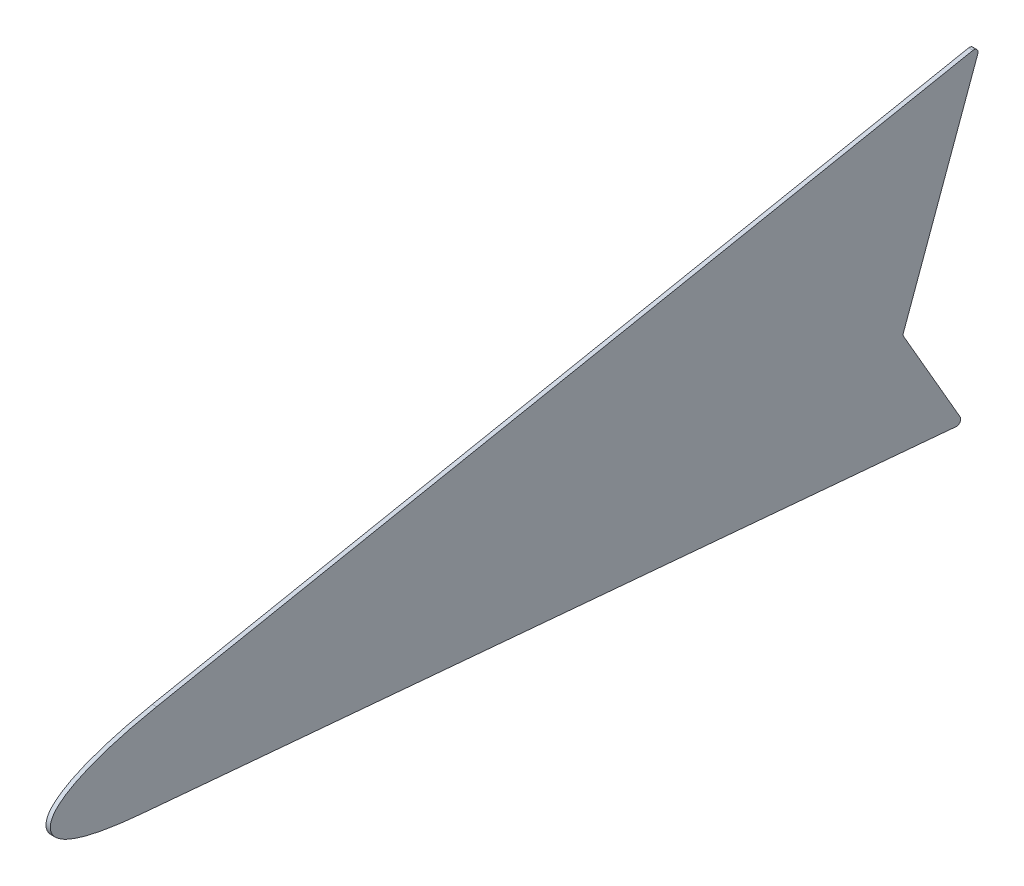
SolidWorks part; units mm, degrees
material "Maple"
ref_plane "Front Plane" through (0, 0, 0) normal (0, 0, 1) x (1, 0, 0)
ref_plane "Top Plane" through (0, 0, 0) normal (0, 1, 0) x (1, 0, 0)
ref_plane "Right Plane" through (0, 0, 0) normal (1, 0, 0) x (0, 0, -1)
other "Configuration Table"
sketch "airfoil" plane through (0, 0, 0) normal (1, 0, 0) x (0, 0, -1)
  line L0 (0, 0) -> (0, -24764.0796) construction
  line L1 (0, 0) -> (24764.0796, 0) construction
  line L2 (400, -0.019) -> (400, -24764.0986) construction
  spline S1 degree 3 poles (399.7808, 0.0037) (400.0541, -0.007) (399.7873, 0.0524) (399.5698, 0.1247) (399.0314, 0.2681) (398.361, 0.4579) (397.4667, 0.704) (396.3877, 1.0028) (395.1106, 1.354) (393.6412, 1.7553) (391.9797, 2.2075) (390.1273, 2.7067) (388.0863, 3.2534) (385.8581, 3.8449) (383.445, 4.48) (380.8487, 5.1558) (378.0717, 5.8707) (375.117, 6.6232) (371.9868, 7.4101) (368.6841, 8.23) (365.2117, 9.0791) (361.5733, 9.9574) (357.7717, 10.8596) (353.8109, 11.785) (349.6943, 12.7299) (345.4261, 13.6926) (341.0101, 14.67) (336.4505, 15.6593) (331.7515, 16.6575) (326.9179, 17.6633) (321.9541, 18.6731) (316.8647, 19.6833) (311.6551, 20.6931) (306.3302, 21.6989) (300.8951, 22.6978) (295.3553, 23.6882) (289.7158, 24.6666) (283.9826, 25.6307) (278.1611, 26.5781) (272.2574, 27.5067) (266.277, 28.413) (260.2261, 29.2967) (254.1107, 30.1529) (247.9371, 30.9818) (241.7114, 31.7791) (235.4401, 32.5443) (229.1296, 33.2746) (222.786, 33.9673) (216.4162, 34.6219) (210.0263, 35.2355) (203.6235, 35.8067) (197.2141, 36.3341) (190.8047, 36.8153) (184.4021, 37.2494) (178.0131, 37.6354) (171.6442, 37.9712) (165.2972, 38.2548) (158.9505, 38.4929) (152.6099, 38.6533) (146.2875, 38.7333) (140.0186, 38.732) (133.8104, 38.6513) (127.6704, 38.4892) (121.6052, 38.2488) (115.622, 37.93) (109.7277, 37.5349) (103.9291, 37.065) (98.2328, 36.5217) (92.6455, 35.9077) (87.1737, 35.2252) (81.8233, 34.4776) (76.6008, 33.6657) (71.5116, 32.7951) (66.562, 31.8667) (61.7572, 30.8857) (57.1026, 29.8545) (52.6032, 28.7774) (48.2641, 27.6573) (44.0894, 26.4993) (40.084, 25.3064) (36.2515, 24.0838) (32.5965, 22.8336) (29.1219, 21.5618) (25.8316, 20.271) (22.7281, 18.9666) (19.8149, 17.6508) (17.0939, 16.3288) (14.5679, 15.0036) (12.239, 13.6786) (10.1085, 12.3581) (8.1785, 11.044) (6.4499, 9.7401) (4.9234, 8.4488) (3.6003, 7.1722) (2.4808, 5.9125) (1.5655, 4.6706) (0.8549, 3.4474) (0.3497, 2.2432) (0.0528, 1.0583) (-0.034, -0.1055) (0.0897, -1.2398) (0.4182, -2.3322) (0.9504, -3.3701) (1.6818, -4.3459) (2.6067, -5.2617) (3.7234, -6.1177) (5.0287, -6.9169) (6.5216, -7.6597) (8.2002, -8.347) (10.0619, -8.981) (12.1056, -9.5604) (14.3281, -10.088) (16.7275, -10.5633) (19.3007, -10.9868) (22.0447, -11.3609) (24.9566, -11.6853) (28.0329, -11.9614) (31.2705, -12.1904) (34.666, -12.3741) (38.2157, -12.5133) (41.9161, -12.6098) (45.7634, -12.6653) (49.7535, -12.6809) (53.883, -12.66) (58.1475, -12.6026) (62.5433, -12.5119) (67.0662, -12.39) (71.7121, -12.2398) (76.4768, -12.062) (81.3559, -11.86) (86.3452, -11.6366) (91.4405, -11.3942) (96.6373, -11.1349) (101.9311, -10.8619) (107.3173, -10.5778) (112.7915, -10.2853) (118.3489, -9.9879) (123.9847, -9.6861) (129.6945, -9.386) (135.4732, -9.0873) (141.316, -8.7944) (147.2177, -8.5093) (153.1732, -8.2342) (159.2057, -7.9715) (165.3147, -7.7212) (171.4933, -7.4556) (177.7074, -7.1838) (183.946, -6.9064) (190.2032, -6.6255) (196.473, -6.3423) (202.7491, -6.0574) (209.0254, -5.7741) (215.296, -5.4912) (221.5545, -5.212) (227.795, -4.937) (234.0111, -4.666) (240.1968, -4.4016) (246.3459, -4.1434) (252.4524, -3.8927) (258.5098, -3.6496) (264.5124, -3.4153) (270.4539, -3.1894) (276.3284, -2.9725) (282.1299, -2.7653) (287.8522, -2.5667) (293.4898, -2.3784) (299.0368, -2.1995) (304.4876, -2.0293) (309.8363, -1.8692) (315.0775, -1.7173) (320.2055, -1.5749) (325.2152, -1.441) (330.1011, -1.3159) (334.8582, -1.1978) (339.4816, -1.088) (343.9662, -0.9862) (348.3071, -0.89) (352.4999, -0.8021) (356.5399, -0.7188) (360.4229, -0.6427) (364.1446, -0.5721) (367.7011, -0.5068) (371.0883, -0.4463) (374.3025, -0.3909) (377.3402, -0.34) (380.1983, -0.2931) (382.8734, -0.2506) (385.3625, -0.2117) (387.6629, -0.1765) (389.7721, -0.1455) (391.6876, -0.117) (393.4074, -0.0923) (394.9291, -0.0701) (396.2527, -0.0522) (397.3716, -0.0354) (398.2989, -0.0246) (398.9952, -0.0113) (399.5522, -0.0105) (399.7808, 0.0037) (400.0541, -0.007) (399.7873, 0.0524) knots -0.001127 -0.000501 -0.000125 0 0.000125 0.000501 0.001127 0.002002 0.003126 0.004497 0.006113 0.007974 0.010078 0.012421 0.015002 0.017818 0.020866 0.024143 0.027646 0.03137 0.035312 0.039469 0.043836 0.048408 0.05318 0.058149 0.063308 0.068652 0.074177 0.079876 0.085744 0.091775 0.097962 0.1043 0.110782 0.117401 0.124151 0.131025 0.138017 0.145118 0.152322 0.159622 0.167011 0.17448 0.182023 0.189631 0.197298 0.205015 0.212775 0.220569 0.228391 0.236232 0.244084 0.251939 0.25979 0.267629 0.275447 0.283237 0.290992 0.298721 0.306502 0.314226 0.321883 0.329466 0.336969 0.344383 0.351701 0.358917 0.366023 0.373012 0.379878 0.386613 0.393211 0.399667 0.405973 0.412124 0.418114 0.423937 0.429588 0.435061 0.440352 0.445457 0.45037 0.455088 0.459606 0.463923 0.468034 0.471937 0.475631 0.479114 0.482385 0.485445 0.488294 0.490935 0.493373 0.495613 0.497665 0.49954 0.501255 0.502835 0.504308 0.505711 0.507087 0.508464 0.509867 0.511338 0.512913 0.51462 0.516481 0.518511 0.520722 0.52312 0.525712 0.5285 0.531486 0.53467 0.538052 0.54163 0.545402 0.549366 0.553519 0.557858 0.56238 0.567079 0.571953 0.576996 0.582206 0.587576 0.593102 0.59878 0.604604 0.610569 0.616669 0.622899 0.629255 0.635729 0.642318 0.649013 0.655811 0.662705 0.669688 0.676756 0.683902 0.691119 0.698401 0.705741 0.713238 0.720798 0.728396 0.736024 0.743674 0.751341 0.759015 0.766689 0.774356 0.782008 0.789638 0.797238 0.804801 0.812319 0.819784 0.827189 0.834527 0.841789 0.84897 0.856061 0.863055 0.869945 0.876724 0.883386 0.889922 0.896327 0.902593 0.908715 0.914685 0.920497 0.926147 0.931626 0.93693 0.942052 0.946989 0.951732 0.956279 0.960625 0.964763 0.968689 0.972401 0.975892 0.979161 0.982201 0.985012 0.987589 0.989929 0.99203 0.993889 0.995505 0.996875 0.997998 0.998873 0.999499 0.999875 1 1.000125 1.000501 1.001127 only from (400, 0) to (400, 0) construction
  spline S2 degree 3 poles (399.113, -0.0415) (400.2203, -0.0144) (399.1258, 0.1563) (398.2295, 0.3934) (396.022, 0.8298) (393.2788, 1.4129) (389.6361, 2.1581) (385.2613, 3.0463) (380.1145, 4.071) (374.2356, 5.2185) (367.6409, 6.4759) (360.3583, 7.829) (352.416, 9.2621) (343.8458, 10.7617) (334.6813, 12.3094) (324.9598, 13.8923) (314.7194, 15.4921) (304.002, 17.095) (292.8506, 18.6831) (281.3109, 20.2429) (269.4294, 21.7574) (257.2549, 23.2132) (244.8374, 24.5932) (232.2279, 25.8854) (219.4786, 27.0728) (206.6425, 28.144) (193.7727, 29.0839) (180.9231, 29.8811) (168.1355, 30.5232) (155.4421, 31.0075) (142.8943, 31.2634) (130.5594, 31.286) (118.5128, 31.0738) (106.8079, 30.6277) (95.496, 29.9512) (84.6272, 29.0517) (74.249, 27.939) (64.4067, 26.6255) (55.1429, 25.1267) (46.4971, 23.4596) (38.5058, 21.6429) (31.2015, 19.6983) (24.6137, 17.646) (18.7672, 15.5082) (13.6836, 13.3047) (9.378, 11.0558) (5.8613, 8.7772) (3.1383, 6.4772) (1.2101, 4.1522) (0.0978, 1.7729) (-0.1149, -0.6368) (0.5777, -2.9531) (2.1358, -5.0611) (4.4694, -6.9597) (7.56, -8.6868) (11.4019, -10.2561) (15.986, -11.6711) (21.297, -12.9303) (27.3143, -14.0326) (34.014, -14.9763) (41.3686, -15.7633) (49.3488, -16.3932) (57.9223, -16.872) (67.0555, -17.2029) (76.7129, -17.3944) (86.857, -17.4543) (97.4491, -17.3946) (108.4486, -17.2263) (119.814, -16.9625) (131.502, -16.6187) (143.4683, -16.2084) (155.6888, -15.7469) (168.1284, -15.2498) (180.7356, -14.6691) (193.4383, -14.025) (206.1735, -13.3296) (218.8895, -12.5939) (231.5349, -11.8294) (244.0582, -11.0443) (256.4083, -10.2493) (268.5344, -9.4516) (280.3869, -8.658) (291.9166, -7.8745) (303.0759, -7.107) (313.8181, -6.3597) (324.0986, -5.6372) (333.8742, -4.9433) (343.1036, -4.2806) (351.748, -3.6538) (359.7706, -3.0659) (367.1372, -2.5202) (373.8169, -2.0198) (379.7791, -1.5684) (385.0044, -1.1695) (389.4506, -0.8253) (393.1553, -0.5418) (395.949, -0.3108) (398.1937, -0.1611) (399.113, -0.0415) (400.2203, -0.0144) (399.1258, 0.1563) knots -0.004573 -0.002036 -0.000509 0 0.000509 0.002036 0.004573 0.008111 0.012633 0.018121 0.024553 0.0319 0.040133 0.049217 0.059115 0.069785 0.081183 0.093262 0.105973 0.119263 0.133076 0.147357 0.162046 0.177082 0.192405 0.20795 0.223653 0.239449 0.255274 0.271062 0.286749 0.302315 0.317731 0.332857 0.347631 0.361995 0.37589 0.389263 0.402061 0.414235 0.42574 0.436535 0.44658 0.455844 0.464299 0.471923 0.478705 0.484642 0.48975 0.494071 0.497691 0.500769 0.503574 0.506378 0.509454 0.513062 0.517356 0.522418 0.528283 0.534965 0.54246 0.550751 0.559818 0.569631 0.580159 0.591365 0.603208 0.615647 0.628635 0.642124 0.656064 0.670403 0.685085 0.700055 0.715334 0.730826 0.746424 0.762064 0.777685 0.793221 0.80861 0.823787 0.83869 0.853258 0.867431 0.881149 0.894355 0.906995 0.919014 0.930362 0.940991 0.950857 0.959916 0.968132 0.975466 0.981889 0.987372 0.991891 0.995427 0.997964 0.999491 1 1.000509 1.002036 1.004573 only from (400, 0) to (400, 0)
  dimension "D1" = 400
sketch "Sketch1" plane through (0, 0, 0) normal (1, 0, 0) x (0, 0, -1)
  line L4 (42.5868, -15.8378) -> (428.8675, -50)
  line L11 (428.8675, -50) -> (400, 0)
  line L13 (49.8714, 24.0968) -> (436.397, 100)
  line L14 (436.397, 100) -> (400, 0)
  line L15 (-200000, 0) -> (224764.0796, 0) construction
  spline S4 degree 3 poles (399.113, -0.0415) (400.2203, -0.0144) (399.1258, 0.1563) (398.2295, 0.3934) (396.022, 0.8298) (393.2788, 1.4129) (389.6361, 2.1581) (385.2613, 3.0463) (380.1145, 4.071) (374.2356, 5.2185) (367.6409, 6.4759) (360.3583, 7.829) (352.416, 9.2621) (343.8458, 10.7617) (334.6813, 12.3094) (324.9598, 13.8923) (314.7194, 15.4921) (304.002, 17.095) (292.8506, 18.6831) (281.3109, 20.2429) (269.4294, 21.7574) (257.2549, 23.2132) (244.8374, 24.5932) (232.2279, 25.8854) (219.4786, 27.0728) (206.6425, 28.144) (193.7727, 29.0839) (180.9231, 29.8811) (168.1355, 30.5232) (155.4421, 31.0075) (142.8943, 31.2634) (130.5594, 31.286) (118.5128, 31.0738) (106.8079, 30.6277) (95.496, 29.9512) (84.6272, 29.0517) (74.249, 27.939) (64.4067, 26.6255) (55.1429, 25.1267) (46.4971, 23.4596) (38.5058, 21.6429) (31.2015, 19.6983) (24.6137, 17.646) (18.7672, 15.5082) (13.6836, 13.3047) (9.378, 11.0558) (5.8613, 8.7772) (3.1383, 6.4772) (1.2101, 4.1522) (0.0978, 1.7729) (-0.1149, -0.6368) (0.5777, -2.9531) (2.1358, -5.0611) (4.4694, -6.9597) (7.56, -8.6868) (11.4019, -10.2561) (15.986, -11.6711) (21.297, -12.9303) (27.3143, -14.0326) (34.014, -14.9763) (41.3686, -15.7633) (49.3488, -16.3932) (57.9223, -16.872) (67.0555, -17.2029) (76.7129, -17.3944) (86.857, -17.4543) (97.4491, -17.3946) (108.4486, -17.2263) (119.814, -16.9625) (131.502, -16.6187) (143.4683, -16.2084) (155.6888, -15.7469) (168.1284, -15.2498) (180.7356, -14.6691) (193.4383, -14.025) (206.1735, -13.3296) (218.8895, -12.5939) (231.5349, -11.8294) (244.0582, -11.0443) (256.4083, -10.2493) (268.5344, -9.4516) (280.3869, -8.658) (291.9166, -7.8745) (303.0759, -7.107) (313.8181, -6.3597) (324.0986, -5.6372) (333.8742, -4.9433) (343.1036, -4.2806) (351.748, -3.6538) (359.7706, -3.0659) (367.1372, -2.5202) (373.8169, -2.0198) (379.7791, -1.5684) (385.0044, -1.1695) (389.4506, -0.8253) (393.1553, -0.5418) (395.949, -0.3108) (398.1937, -0.1611) (399.113, -0.0415) (400.2203, -0.0144) (399.1258, 0.1563) knots -0.004573 -0.002036 -0.000509 0 0.000509 0.002036 0.004573 0.008111 0.012633 0.018121 0.024553 0.0319 0.040133 0.049217 0.059115 0.069785 0.081183 0.093262 0.105973 0.119263 0.133076 0.147357 0.162046 0.177082 0.192405 0.20795 0.223653 0.239449 0.255274 0.271062 0.286749 0.302315 0.317731 0.332857 0.347631 0.361995 0.37589 0.389263 0.402061 0.414235 0.42574 0.436535 0.44658 0.455844 0.464299 0.471923 0.478705 0.484642 0.48975 0.494071 0.497691 0.500769 0.503574 0.506378 0.509454 0.513062 0.517356 0.522418 0.528283 0.534965 0.54246 0.550751 0.559818 0.569631 0.580159 0.591365 0.603208 0.615647 0.628635 0.642124 0.656064 0.670403 0.685085 0.700055 0.715334 0.730826 0.746424 0.762064 0.777685 0.793221 0.80861 0.823787 0.83869 0.853258 0.867431 0.881149 0.894355 0.906995 0.919014 0.930362 0.940991 0.950857 0.959916 0.968132 0.975466 0.981889 0.987372 0.991891 0.995427 0.997964 0.999491 1 1.000509 1.002036 1.004573 only from (400, 0) to (400, 0)
  spline S5 degree 3 poles (49.8714, 24.0968) (48.6818, 23.8632) (44.8141, 23.077) (38.5058, 21.6429) (31.2015, 19.6983) (24.6137, 17.646) (18.7672, 15.5082) (13.6836, 13.3047) (9.378, 11.0558) (5.8613, 8.7772) (3.1383, 6.4772) (1.2101, 4.1522) (0.0978, 1.7729) (-0.1149, -0.6368) (0.5777, -2.9531) (2.1358, -5.0611) (4.4694, -6.9597) (7.56, -8.6868) (11.4019, -10.2561) (15.986, -11.6711) (21.297, -12.9303) (27.3143, -14.0326) (34.014, -14.9763) (39.1842, -15.5296) (42.1143, -15.796) (42.5868, -15.8378) knots 0.43208 0.43208 0.43208 0.43208 0.436535 0.44658 0.455844 0.464299 0.471923 0.478705 0.484642 0.48975 0.494071 0.497691 0.500769 0.503574 0.506378 0.509454 0.513062 0.517356 0.522418 0.528283 0.534965 0.54246 0.550751 0.559818 0.561561 0.561561 0.561561 0.561561
  point P0 (389.93, 0)
  dimension "D2" = 100
  dimension "D3" = 50
  dimension "D4" = 70
  dimension "D5" = 60
  dimension "D1" = 0
extrude "Boss-Extrude1" add sketch "Sketch1" along normal blind 2
fillet "Fillet1" radius 2 3 edges at (1, 0, -400) (1, -50, -428.8675) (1, 100, -436.397)
equation "\"chord\"= 400mm"
equation "\"D1@airfoil\" = \"chord\""
equation "\"D1@spars\"= 0.25 * \"chord\""
equation "\"skeletonization offset\"= 4"
equation "\"truss angle\"= 45"
equation "\"D2@spars\"= \"chord\" * 0.7"
